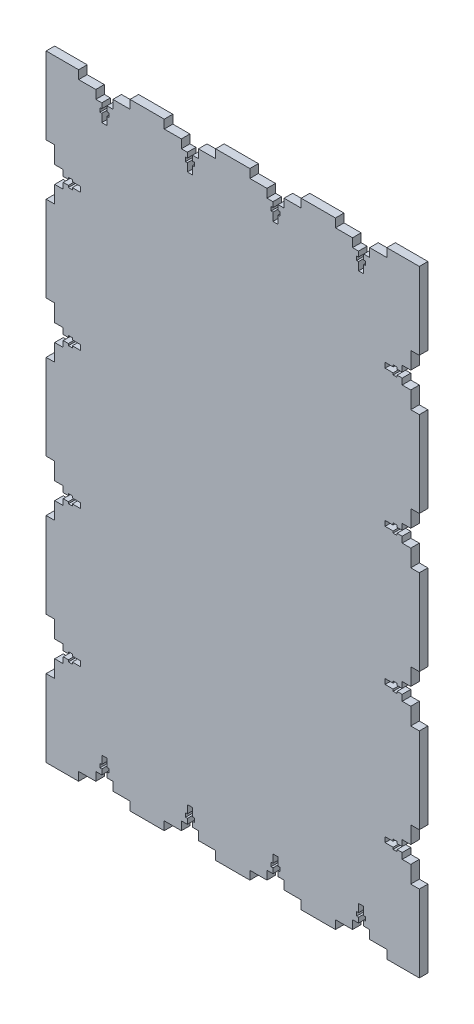
SolidWorks part; units mm, degrees
ref_plane "Front Plane" through (0, 0, 0) normal (0, 0, 1) x (1, 0, 0)
ref_plane "Top Plane" through (0, 0, 0) normal (0, 1, 0) x (1, 0, 0)
ref_plane "Right Plane" through (0, 0, 0) normal (1, 0, 0) x (0, 0, -1)
sketch "Sketch1" plane through (0, 0, 0) normal (0, 0, 1) x (1, 0, 0)
  line L0 (0.4643, -20.0606) -> (0.4643, 357.2079) construction
  line L1 (109.4643, 159.9394) -> (90.4643, 159.9394)
  line L2 (90.4643, 159.9394) -> (90.4643, 154.9394)
  line L3 (90.4643, 154.9394) -> (80.4643, 154.9394)
  line L4 (60.4643, 154.9394) -> (60.4643, 159.9394)
  line L5 (60.4643, 159.9394) -> (40.4643, 159.9394)
  line L6 (40.4643, 159.9394) -> (40.4643, 154.9394)
  line L8 (-9.5357, 154.9394) -> (-9.5357, 159.9394)
  line L9 (-9.5357, 159.9394) -> (10.4643, 159.9394)
  line L10 (10.4643, 159.9394) -> (10.4643, 154.9394)
  line L12 (-39.5357, 154.9394) -> (-39.5357, 159.9394)
  line L13 (-39.5357, 159.9394) -> (-59.5357, 159.9394)
  line L14 (-59.5357, 159.9394) -> (-59.5357, 154.9394)
  line L15 (-59.5357, 154.9394) -> (-69.5357, 154.9394)
  line L16 (-89.5357, 154.9394) -> (-89.5357, 159.9394)
  line L17 (-89.5357, 159.9394) -> (-108.5357, 159.9394)
  line L18 (109.4643, 159.9394) -> (109.4643, 114.9394)
  line L19 (109.4643, 114.9394) -> (104.4643, 114.9394)
  line L20 (104.4643, 114.9394) -> (104.4643, 104.9394)
  line L21 (104.4643, 84.9394) -> (109.4643, 84.9394)
  line L22 (109.4643, 84.9394) -> (109.4643, 34.9394)
  line L23 (109.4643, 34.9394) -> (104.4643, 34.9394)
  line L24 (104.4643, 34.9394) -> (104.4643, 24.9394)
  line L25 (104.4643, 4.9394) -> (109.4643, 4.9394)
  line L26 (109.4643, 4.9394) -> (109.4643, -45.0606)
  line L27 (109.4643, -45.0606) -> (104.4643, -45.0606)
  line L28 (104.4643, -45.0606) -> (104.4643, -55.0606)
  line L29 (104.4643, -75.0606) -> (109.4643, -75.0606)
  line L30 (109.4643, -75.0606) -> (109.4643, -125.0606)
  line L31 (109.4643, -125.0606) -> (104.4643, -125.0606)
  line L32 (104.4643, -125.0606) -> (104.4643, -135.0606)
  line L33 (104.4643, -155.0606) -> (109.4643, -155.0606)
  line L34 (109.4643, -155.0606) -> (109.4643, -200.0606)
  line L35 (-108.5357, -155.0606) -> (-108.5357, -200.0606)
  line L36 (-103.5357, -155.0606) -> (-108.5357, -155.0606)
  line L37 (-103.5357, -125.0606) -> (-103.5357, -135.0606)
  line L38 (-108.5357, -125.0606) -> (-103.5357, -125.0606)
  line L39 (-108.5357, -75.0606) -> (-108.5357, -125.0606)
  line L40 (-103.5357, -75.0606) -> (-108.5357, -75.0606)
  line L41 (-103.5357, -45.0606) -> (-103.5357, -55.0606)
  line L42 (-108.5357, -45.0606) -> (-103.5357, -45.0606)
  line L43 (-108.5357, 4.9394) -> (-108.5357, -45.0606)
  line L44 (-103.5357, 4.9394) -> (-108.5357, 4.9394)
  line L45 (-103.5357, 34.9394) -> (-103.5357, 24.9394)
  line L46 (-108.5357, 34.9394) -> (-103.5357, 34.9394)
  line L47 (-108.5357, 84.9394) -> (-108.5357, 34.9394)
  line L48 (-103.5357, 84.9394) -> (-108.5357, 84.9394)
  line L49 (-103.5357, 114.9394) -> (-103.5357, 104.9394)
  line L50 (-108.5357, 114.9394) -> (-103.5357, 114.9394)
  line L51 (-108.5357, 159.9394) -> (-108.5357, 114.9394)
  line L52 (0.4643, -20.0606) -> (119.5649, -20.0606) construction
  line L53 (109.4643, -200.0606) -> (90.4643, -200.0606)
  line L54 (-89.5357, -200.0606) -> (-108.5357, -200.0606)
  line L55 (-89.5357, -195.0606) -> (-89.5357, -200.0606)
  line L56 (-59.5357, -195.0606) -> (-69.5357, -195.0606)
  line L57 (-59.5357, -200.0606) -> (-59.5357, -195.0606)
  line L58 (-39.5357, -200.0606) -> (-59.5357, -200.0606)
  line L59 (-39.5357, -195.0606) -> (-39.5357, -200.0606)
  line L61 (10.4643, -200.0606) -> (10.4643, -195.0606)
  line L62 (-9.5357, -200.0606) -> (10.4643, -200.0606)
  line L63 (-9.5357, -195.0606) -> (-9.5357, -200.0606)
  line L65 (40.4643, -200.0606) -> (40.4643, -195.0606)
  line L66 (60.4643, -200.0606) -> (40.4643, -200.0606)
  line L67 (60.4643, -195.0606) -> (60.4643, -200.0606)
  line L68 (90.4643, -195.0606) -> (80.4643, -195.0606)
  line L69 (90.4643, -200.0606) -> (90.4643, -195.0606)
  line L75 (-39.5357, 154.9394) -> (-29.5357, 154.9394)
  line L76 (10.4643, 154.9394) -> (20.4643, 154.9394)
  line L81 (-39.5357, -195.0606) -> (-29.5357, -195.0606)
  line L82 (10.4643, -195.0606) -> (20.4643, -195.0606)
  line L84 (-26.0357, -190.0606) -> (-29.5357, -190.0606)
  line L85 (90.4643, 154.9394) -> (90.4643, 159.9394) construction
  line L88 (57.0106, -0.0606) -> (-42.9839, -0.0606) construction
  line L89 (10.4643, 154.9394) -> (10.4643, 159.9394) construction
  line L90 (-29.5357, -195.0606) -> (-29.5357, -190.0606)
  line L91 (-19.5357, -190.0606) -> (-19.5357, -195.0606)
  line L92 (-26.0357, -190.0606) -> (-26.0357, -187.0606)
  line L93 (-27.1357, -187.0606) -> (-27.1357, -184.7606)
  line L94 (-21.9357, -187.0606) -> (-23.0357, -187.0606)
  line L95 (-26.0357, -184.7606) -> (-26.0357, -180.0606)
  line L96 (-26.0357, -180.0606) -> (-23.0357, -180.0606)
  line L97 (-23.0357, -180.0606) -> (-23.0357, -184.7606)
  line L98 (-26.0357, -187.0606) -> (-27.1357, -187.0606)
  line L99 (-21.9357, -184.7606) -> (-21.9357, -187.0606)
  line L100 (-27.1357, -184.7606) -> (-26.0357, -184.7606)
  line L101 (-23.0357, -187.0606) -> (-23.0357, -190.0606)
  line L102 (-23.0357, -190.0606) -> (-19.5357, -190.0606)
  line L103 (-23.0357, -184.7606) -> (-21.9357, -184.7606)
  line L104 (-98.5357, -138.5606) -> (-98.5357, -135.0606)
  line L105 (-103.5357, -135.0606) -> (-98.5357, -135.0606)
  line L106 (-98.5357, -145.0606) -> (-103.5357, -145.0606)
  line L107 (-98.5357, -138.5606) -> (-95.5357, -138.5606)
  line L108 (-95.5357, -137.4606) -> (-93.2357, -137.4606)
  line L109 (-95.5357, -142.6606) -> (-95.5357, -141.5606)
  line L110 (-93.2357, -138.5606) -> (-88.5357, -138.5606)
  line L111 (-88.5357, -138.5606) -> (-88.5357, -141.5606)
  line L112 (-88.5357, -141.5606) -> (-93.2357, -141.5606)
  line L113 (-95.5357, -138.5606) -> (-95.5357, -137.4606)
  line L114 (-93.2357, -142.6606) -> (-95.5357, -142.6606)
  line L115 (-93.2357, -137.4606) -> (-93.2357, -138.5606)
  line L116 (-95.5357, -141.5606) -> (-98.5357, -141.5606)
  line L117 (-98.5357, -141.5606) -> (-98.5357, -145.0606)
  line L118 (-93.2357, -141.5606) -> (-93.2357, -142.6606)
  line L119 (-76.0357, -190.0606) -> (-79.5357, -190.0606)
  line L120 (-79.5357, -195.0606) -> (-79.5357, -190.0606)
  line L121 (-69.5357, -190.0606) -> (-69.5357, -195.0606)
  line L122 (-76.0357, -190.0606) -> (-76.0357, -187.0606)
  line L123 (-77.1357, -187.0606) -> (-77.1357, -184.7606)
  line L124 (-71.9357, -187.0606) -> (-73.0357, -187.0606)
  line L125 (-76.0357, -184.7606) -> (-76.0357, -180.0606)
  line L126 (-76.0357, -180.0606) -> (-73.0357, -180.0606)
  line L127 (-73.0357, -180.0606) -> (-73.0357, -184.7606)
  line L128 (-76.0357, -187.0606) -> (-77.1357, -187.0606)
  line L129 (-71.9357, -184.7606) -> (-71.9357, -187.0606)
  line L130 (-77.1357, -184.7606) -> (-76.0357, -184.7606)
  line L131 (-73.0357, -187.0606) -> (-73.0357, -190.0606)
  line L132 (-73.0357, -190.0606) -> (-69.5357, -190.0606)
  line L133 (-73.0357, -184.7606) -> (-71.9357, -184.7606)
  line L134 (-98.5357, -58.5606) -> (-98.5357, -55.0606)
  line L135 (-103.5357, -55.0606) -> (-98.5357, -55.0606)
  line L136 (-98.5357, -65.0606) -> (-103.5357, -65.0606)
  line L137 (-98.5357, -58.5606) -> (-95.5357, -58.5606)
  line L138 (-95.5357, -57.4606) -> (-93.2357, -57.4606)
  line L139 (-95.5357, -62.6606) -> (-95.5357, -61.5606)
  line L140 (-93.2357, -58.5606) -> (-88.5357, -58.5606)
  line L141 (-88.5357, -58.5606) -> (-88.5357, -61.5606)
  line L142 (-88.5357, -61.5606) -> (-93.2357, -61.5606)
  line L143 (-95.5357, -58.5606) -> (-95.5357, -57.4606)
  line L144 (-93.2357, -62.6606) -> (-95.5357, -62.6606)
  line L145 (-93.2357, -57.4606) -> (-93.2357, -58.5606)
  line L146 (-95.5357, -61.5606) -> (-98.5357, -61.5606)
  line L147 (-98.5357, -61.5606) -> (-98.5357, -65.0606)
  line L148 (-93.2357, -61.5606) -> (-93.2357, -62.6606)
  line L149 (23.9643, -184.7606) -> (22.8643, -184.7606)
  line L150 (23.9643, -190.0606) -> (20.4643, -190.0606)
  line L151 (23.9643, -187.0606) -> (23.9643, -190.0606)
  line L152 (28.0643, -184.7606) -> (26.9643, -184.7606)
  line L153 (22.8643, -184.7606) -> (22.8643, -187.0606)
  line L154 (26.9643, -187.0606) -> (28.0643, -187.0606)
  line L155 (23.9643, -180.0606) -> (23.9643, -184.7606)
  line L156 (26.9643, -180.0606) -> (23.9643, -180.0606)
  line L157 (26.9643, -184.7606) -> (26.9643, -180.0606)
  line L158 (22.8643, -187.0606) -> (23.9643, -187.0606)
  line L159 (28.0643, -187.0606) -> (28.0643, -184.7606)
  line L160 (26.9643, -190.0606) -> (26.9643, -187.0606)
  line L161 (20.4643, -190.0606) -> (20.4643, -195.0606)
  line L162 (30.4643, -195.0606) -> (30.4643, -190.0606)
  line L163 (26.9643, -190.0606) -> (30.4643, -190.0606)
  line L164 (73.9643, -184.7606) -> (72.8643, -184.7606)
  line L165 (73.9643, -190.0606) -> (70.4643, -190.0606)
  line L166 (73.9643, -187.0606) -> (73.9643, -190.0606)
  line L167 (78.0643, -184.7606) -> (76.9643, -184.7606)
  line L168 (72.8643, -184.7606) -> (72.8643, -187.0606)
  line L169 (76.9643, -187.0606) -> (78.0643, -187.0606)
  line L170 (73.9643, -180.0606) -> (73.9643, -184.7606)
  line L171 (76.9643, -180.0606) -> (73.9643, -180.0606)
  line L172 (76.9643, -184.7606) -> (76.9643, -180.0606)
  line L173 (72.8643, -187.0606) -> (73.9643, -187.0606)
  line L174 (78.0643, -187.0606) -> (78.0643, -184.7606)
  line L175 (76.9643, -190.0606) -> (76.9643, -187.0606)
  line L176 (70.4643, -190.0606) -> (70.4643, -195.0606)
  line L177 (80.4643, -195.0606) -> (80.4643, -190.0606)
  line L178 (76.9643, -190.0606) -> (80.4643, -190.0606)
  line L179 (94.1643, -141.5606) -> (94.1643, -142.6606)
  line L180 (99.4643, -141.5606) -> (99.4643, -145.0606)
  line L181 (96.4643, -141.5606) -> (99.4643, -141.5606)
  line L182 (94.1643, -137.4606) -> (94.1643, -138.5606)
  line L183 (94.1643, -142.6606) -> (96.4643, -142.6606)
  line L184 (96.4643, -138.5606) -> (96.4643, -137.4606)
  line L185 (89.4643, -141.5606) -> (94.1643, -141.5606)
  line L186 (89.4643, -138.5606) -> (89.4643, -141.5606)
  line L187 (94.1643, -138.5606) -> (89.4643, -138.5606)
  line L188 (96.4643, -142.6606) -> (96.4643, -141.5606)
  line L189 (96.4643, -137.4606) -> (94.1643, -137.4606)
  line L190 (99.4643, -138.5606) -> (96.4643, -138.5606)
  line L191 (99.4643, -145.0606) -> (104.4643, -145.0606)
  line L192 (104.4643, -135.0606) -> (99.4643, -135.0606)
  line L193 (99.4643, -138.5606) -> (99.4643, -135.0606)
  line L194 (94.1643, -61.5606) -> (94.1643, -62.6606)
  line L195 (99.4643, -61.5606) -> (99.4643, -65.0606)
  line L196 (96.4643, -61.5606) -> (99.4643, -61.5606)
  line L197 (94.1643, -57.4606) -> (94.1643, -58.5606)
  line L198 (94.1643, -62.6606) -> (96.4643, -62.6606)
  line L199 (96.4643, -58.5606) -> (96.4643, -57.4606)
  line L200 (89.4643, -61.5606) -> (94.1643, -61.5606)
  line L201 (89.4643, -58.5606) -> (89.4643, -61.5606)
  line L202 (94.1643, -58.5606) -> (89.4643, -58.5606)
  line L203 (96.4643, -62.6606) -> (96.4643, -61.5606)
  line L204 (96.4643, -57.4606) -> (94.1643, -57.4606)
  line L205 (99.4643, -58.5606) -> (96.4643, -58.5606)
  line L206 (99.4643, -65.0606) -> (104.4643, -65.0606)
  line L207 (104.4643, -55.0606) -> (99.4643, -55.0606)
  line L208 (99.4643, -58.5606) -> (99.4643, -55.0606)
  line L209 (70.4643, 149.9394) -> (70.4643, 154.9394)
  line L210 (73.9643, 149.9394) -> (70.4643, 149.9394)
  line L211 (76.9643, 149.9394) -> (80.4643, 149.9394)
  line L212 (80.4643, 154.9394) -> (80.4643, 149.9394)
  line L213 (76.9643, 149.9394) -> (76.9643, 146.9394)
  line L214 (78.0643, 146.9394) -> (78.0643, 144.6394)
  line L215 (72.8643, 146.9394) -> (73.9643, 146.9394)
  line L216 (76.9643, 144.6394) -> (76.9643, 139.9394)
  line L217 (76.9643, 139.9394) -> (73.9643, 139.9394)
  line L218 (73.9643, 139.9394) -> (73.9643, 144.6394)
  line L219 (76.9643, 146.9394) -> (78.0643, 146.9394)
  line L220 (72.8643, 144.6394) -> (72.8643, 146.9394)
  line L221 (78.0643, 144.6394) -> (76.9643, 144.6394)
  line L222 (73.9643, 146.9394) -> (73.9643, 149.9394)
  line L223 (73.9643, 144.6394) -> (72.8643, 144.6394)
  line L224 (26.9643, 149.9394) -> (30.4643, 149.9394)
  line L225 (30.4643, 154.9394) -> (30.4643, 149.9394)
  line L226 (20.4643, 149.9394) -> (20.4643, 154.9394)
  line L227 (26.9643, 149.9394) -> (26.9643, 146.9394)
  line L228 (28.0643, 146.9394) -> (28.0643, 144.6394)
  line L229 (22.8643, 146.9394) -> (23.9643, 146.9394)
  line L230 (26.9643, 144.6394) -> (26.9643, 139.9394)
  line L231 (26.9643, 139.9394) -> (23.9643, 139.9394)
  line L232 (23.9643, 139.9394) -> (23.9643, 144.6394)
  line L233 (26.9643, 146.9394) -> (28.0643, 146.9394)
  line L234 (22.8643, 144.6394) -> (22.8643, 146.9394)
  line L235 (28.0643, 144.6394) -> (26.9643, 144.6394)
  line L236 (23.9643, 146.9394) -> (23.9643, 149.9394)
  line L237 (23.9643, 149.9394) -> (20.4643, 149.9394)
  line L238 (23.9643, 144.6394) -> (22.8643, 144.6394)
  line L239 (-23.0357, 144.6394) -> (-21.9357, 144.6394)
  line L240 (-23.0357, 149.9394) -> (-19.5357, 149.9394)
  line L241 (-23.0357, 146.9394) -> (-23.0357, 149.9394)
  line L242 (-27.1357, 144.6394) -> (-26.0357, 144.6394)
  line L243 (-21.9357, 144.6394) -> (-21.9357, 146.9394)
  line L244 (-26.0357, 146.9394) -> (-27.1357, 146.9394)
  line L245 (-23.0357, 139.9394) -> (-23.0357, 144.6394)
  line L246 (-26.0357, 139.9394) -> (-23.0357, 139.9394)
  line L247 (-26.0357, 144.6394) -> (-26.0357, 139.9394)
  line L248 (-21.9357, 146.9394) -> (-23.0357, 146.9394)
  line L249 (-27.1357, 146.9394) -> (-27.1357, 144.6394)
  line L250 (-26.0357, 149.9394) -> (-26.0357, 146.9394)
  line L251 (-19.5357, 149.9394) -> (-19.5357, 154.9394)
  line L252 (-29.5357, 154.9394) -> (-29.5357, 149.9394)
  line L253 (-26.0357, 149.9394) -> (-29.5357, 149.9394)
  line L254 (-73.0357, 144.6394) -> (-71.9357, 144.6394)
  line L255 (-73.0357, 149.9394) -> (-69.5357, 149.9394)
  line L256 (-73.0357, 146.9394) -> (-73.0357, 149.9394)
  line L257 (-77.1357, 144.6394) -> (-76.0357, 144.6394)
  line L258 (-71.9357, 144.6394) -> (-71.9357, 146.9394)
  line L259 (-76.0357, 146.9394) -> (-77.1357, 146.9394)
  line L260 (-73.0357, 139.9394) -> (-73.0357, 144.6394)
  line L261 (-76.0357, 139.9394) -> (-73.0357, 139.9394)
  line L262 (-76.0357, 144.6394) -> (-76.0357, 139.9394)
  line L263 (-71.9357, 146.9394) -> (-73.0357, 146.9394)
  line L264 (-77.1357, 146.9394) -> (-77.1357, 144.6394)
  line L265 (-76.0357, 149.9394) -> (-76.0357, 146.9394)
  line L266 (-69.5357, 149.9394) -> (-69.5357, 154.9394)
  line L267 (-79.5357, 154.9394) -> (-79.5357, 149.9394)
  line L268 (-76.0357, 149.9394) -> (-79.5357, 149.9394)
  line L269 (99.4643, 98.4394) -> (99.4643, 94.9394)
  line L270 (104.4643, 94.9394) -> (99.4643, 94.9394)
  line L271 (99.4643, 104.9394) -> (104.4643, 104.9394)
  line L272 (99.4643, 98.4394) -> (96.4643, 98.4394)
  line L273 (96.4643, 97.3394) -> (94.1643, 97.3394)
  line L274 (96.4643, 102.5394) -> (96.4643, 101.4394)
  line L275 (94.1643, 98.4394) -> (89.4643, 98.4394)
  line L276 (89.4643, 98.4394) -> (89.4643, 101.4394)
  line L277 (89.4643, 101.4394) -> (94.1643, 101.4394)
  line L278 (96.4643, 98.4394) -> (96.4643, 97.3394)
  line L279 (94.1643, 102.5394) -> (96.4643, 102.5394)
  line L280 (94.1643, 97.3394) -> (94.1643, 98.4394)
  line L281 (96.4643, 101.4394) -> (99.4643, 101.4394)
  line L282 (99.4643, 101.4394) -> (99.4643, 104.9394)
  line L283 (94.1643, 101.4394) -> (94.1643, 102.5394)
  line L284 (-93.2357, 101.4394) -> (-93.2357, 102.5394)
  line L285 (-98.5357, 101.4394) -> (-98.5357, 104.9394)
  line L286 (-95.5357, 101.4394) -> (-98.5357, 101.4394)
  line L287 (-93.2357, 97.3394) -> (-93.2357, 98.4394)
  line L288 (-93.2357, 102.5394) -> (-95.5357, 102.5394)
  line L289 (-95.5357, 98.4394) -> (-95.5357, 97.3394)
  line L290 (-88.5357, 101.4394) -> (-93.2357, 101.4394)
  line L291 (-88.5357, 98.4394) -> (-88.5357, 101.4394)
  line L292 (-93.2357, 98.4394) -> (-88.5357, 98.4394)
  line L293 (-95.5357, 102.5394) -> (-95.5357, 101.4394)
  line L294 (-95.5357, 97.3394) -> (-93.2357, 97.3394)
  line L295 (-98.5357, 98.4394) -> (-95.5357, 98.4394)
  line L296 (-98.5357, 104.9394) -> (-103.5357, 104.9394)
  line L297 (-103.5357, 94.9394) -> (-98.5357, 94.9394)
  line L298 (-98.5357, 98.4394) -> (-98.5357, 94.9394)
  line L299 (-103.5357, 84.9394) -> (-103.5357, 94.9394)
  line L300 (104.4643, 84.9394) -> (104.4643, 94.9394)
  line L301 (99.4643, 18.4394) -> (99.4643, 14.9394)
  line L302 (104.4643, 14.9394) -> (99.4643, 14.9394)
  line L303 (99.4643, 24.9394) -> (104.4643, 24.9394)
  line L304 (99.4643, 18.4394) -> (96.4643, 18.4394)
  line L305 (96.4643, 17.3394) -> (94.1643, 17.3394)
  line L306 (96.4643, 22.5394) -> (96.4643, 21.4394)
  line L307 (94.1643, 18.4394) -> (89.4643, 18.4394)
  line L308 (89.4643, 18.4394) -> (89.4643, 21.4394)
  line L309 (89.4643, 21.4394) -> (94.1643, 21.4394)
  line L310 (96.4643, 18.4394) -> (96.4643, 17.3394)
  line L311 (94.1643, 22.5394) -> (96.4643, 22.5394)
  line L312 (94.1643, 17.3394) -> (94.1643, 18.4394)
  line L313 (96.4643, 21.4394) -> (99.4643, 21.4394)
  line L314 (99.4643, 21.4394) -> (99.4643, 24.9394)
  line L315 (94.1643, 21.4394) -> (94.1643, 22.5394)
  line L316 (-93.2357, 21.4394) -> (-93.2357, 22.5394)
  line L317 (-98.5357, 21.4394) -> (-98.5357, 24.9394)
  line L318 (-95.5357, 21.4394) -> (-98.5357, 21.4394)
  line L319 (-93.2357, 17.3394) -> (-93.2357, 18.4394)
  line L320 (-93.2357, 22.5394) -> (-95.5357, 22.5394)
  line L321 (-95.5357, 18.4394) -> (-95.5357, 17.3394)
  line L322 (-88.5357, 21.4394) -> (-93.2357, 21.4394)
  line L323 (-88.5357, 18.4394) -> (-88.5357, 21.4394)
  line L324 (-93.2357, 18.4394) -> (-88.5357, 18.4394)
  line L325 (-95.5357, 22.5394) -> (-95.5357, 21.4394)
  line L326 (-95.5357, 17.3394) -> (-93.2357, 17.3394)
  line L327 (-98.5357, 18.4394) -> (-95.5357, 18.4394)
  line L328 (-98.5357, 24.9394) -> (-103.5357, 24.9394)
  line L329 (-103.5357, 14.9394) -> (-98.5357, 14.9394)
  line L330 (-98.5357, 18.4394) -> (-98.5357, 14.9394)
  line L331 (-103.5357, 4.9394) -> (-103.5357, 14.9394)
  line L332 (104.4643, 4.9394) -> (104.4643, 14.9394)
  line L333 (-79.5357, 154.9394) -> (-89.5357, 154.9394)
  line L334 (-19.5357, 154.9394) -> (-9.5357, 154.9394)
  line L335 (30.4643, 154.9394) -> (40.4643, 154.9394)
  line L336 (-103.5357, 94.9394) -> (-103.5357, 84.9394)
  line L337 (-103.5357, 104.9394) -> (-103.5357, 114.9394)
  line L338 (70.4643, 154.9394) -> (60.4643, 154.9394)
  line L339 (104.4643, 94.9394) -> (104.4643, 84.9394)
  line L340 (104.4643, 104.9394) -> (104.4643, 114.9394)
  line L341 (104.4643, 14.9394) -> (104.4643, 4.9394)
  line L342 (104.4643, -65.0606) -> (104.4643, -75.0606)
  line L343 (104.4643, -145.0606) -> (104.4643, -155.0606)
  line L344 (70.4643, -195.0606) -> (60.4643, -195.0606)
  line L345 (30.4643, -195.0606) -> (40.4643, -195.0606)
  line L346 (-19.5357, -195.0606) -> (-9.5357, -195.0606)
  line L347 (-79.5357, -195.0606) -> (-89.5357, -195.0606)
  line L348 (-103.5357, -145.0606) -> (-103.5357, -155.0606)
  line L349 (-103.5357, -65.0606) -> (-103.5357, -75.0606)
  line L350 (104.4643, 24.9394) -> (104.4643, 34.9394)
  line L351 (-103.5357, 14.9394) -> (-103.5357, 4.9394)
  line L352 (-103.5357, 24.9394) -> (-103.5357, 34.9394)
  dimension "D1" = 30
  dimension "D2" = 30
  dimension "D3" = 5
  dimension "D4" = 10
  dimension "D5" = 218
  dimension "D6" = 20
  dimension "D7" = 50
  dimension "D8" = 10
  dimension "D9" = 10
  dimension "D10" = 10
extrude "Boss-Extrude1" add sketch "Sketch1" along normal blind 5 contours L136 L349 L40 L39 L38 L37 L105 L104 L107 L113 L108 L115 L110 L111 L112 L118 L114 L109 L116 L117 L106 L348 L36 L35 L54 L55 L347 L120 L119 L122 L128 L123 L130 L125 L126 L127 L133 L129 L124 L131 L132 L121 L56 L57 L58 L59 L81 L90 L84 L92 L98
